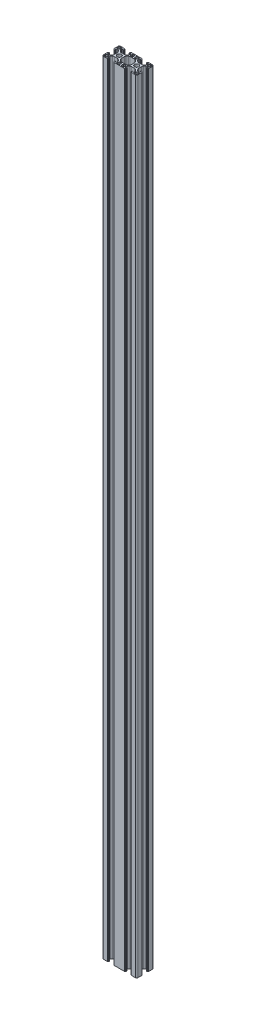
SolidWorks part; units mm, degrees
ref_plane "Спереди" through (0, 0, 0) normal (0, 0, 1) x (1, 0, 0)
ref_plane "Сверху" through (0, 0, 0) normal (0, 1, 0) x (1, 0, 0)
ref_plane "Справа" through (0, 0, 0) normal (1, 0, 0) x (0, 0, -1)
sketch "Эскиз2" plane through (0, 0, 0) normal (0, 1, 0) x (1, 0, 0)
  line L0 (-2.2449, 7.8949) -> (-0.7449, 6.3949) construction
  line L1 (19.2551, 9.3949) -> (16.2551, 6.3949) construction
  line L2 (-9.8449, 0.2949) -> (0.1551, 10.2949) construction
  line L3 (10.1551, 4.2949) -> (12.0538, 4.2949)
  line L4 (10.1551, 0.2949) -> (20.1551, 10.2949) construction
  line L5 (17.7551, 7.8949) -> (16.2551, 9.3949) construction
  line L6 (13.4681, 4.8807) -> (14.7693, 6.1819)
  line L7 (17.0551, 6.3949) -> (18.4551, 6.3949)
  line L8 (16.2551, 7.1949) -> (16.2551, 8.5949)
  line L9 (18.4551, 9.3949) -> (17.0551, 9.3949)
  line L10 (15.3551, 8.4949) -> (15.3551, 7.5961)
  line L11 (13.9183, 8.3681) -> (14.3986, 8.8485)
  line L12 (13.3551, 9.844) -> (13.8551, 9.844)
  line L13 (13.7415, 8.2949) -> (13.4551, 8.2949)
  line L14 (14.7522, 8.9949) -> (14.8551, 8.9949)
  line L15 (13.8551, 10.1449) -> (13.8551, 9.844)
  line L16 (13.2051, 9.694) -> (13.2051, 8.5449)
  line L17 (18.6551, 10.2949) -> (14.0051, 10.2949)
  line L18 (19.2551, 8.5949) -> (19.2551, 7.1949)
  line L19 (20.1551, 8.7949) -> (20.1551, 4.1449)
  line L20 (19.5541, 3.3449) -> (18.4051, 3.3449)
  line L21 (20.0051, 3.9949) -> (19.7041, 3.9949)
  line L22 (18.8551, 4.892) -> (18.8551, 4.9949)
  line L23 (18.1551, 3.8814) -> (18.1551, 3.5949)
  line L24 (19.7041, 3.4949) -> (19.7041, 3.9949)
  line L25 (18.2283, 4.0581) -> (18.7086, 4.5385)
  line L26 (18.3551, 5.4949) -> (17.4563, 5.4949)
  line L27 (14.7409, 3.6079) -> (16.0421, 4.9091)
  line L28 (14.1551, 0.2949) -> (14.1551, 2.1937)
  line L29 (14.1551, 0.2949) -> (14.1551, -1.6039)
  line L30 (14.7409, -3.0181) -> (16.0421, -4.3193)
  line L31 (16.2551, -6.6051) -> (16.2551, -8.0051)
  line L32 (17.0551, -5.8051) -> (18.4551, -5.8051)
  line L33 (19.2551, -8.0051) -> (19.2551, -6.6051)
  line L34 (18.3551, -4.9051) -> (17.4563, -4.9051)
  line L35 (18.2283, -3.4683) -> (18.7086, -3.9486)
  line L36 (19.7041, -2.9051) -> (19.7041, -3.4051)
  line L37 (18.1551, -3.2915) -> (18.1551, -3.0051)
  line L38 (18.8551, -4.3022) -> (18.8551, -4.4051)
  line L39 (20.0051, -3.4051) -> (19.7041, -3.4051)
  line L40 (19.5541, -2.7551) -> (18.4051, -2.7551)
  line L41 (20.1551, -8.2051) -> (20.1551, -3.5551)
  line L42 (18.4551, -8.8051) -> (17.0551, -8.8051)
  line L43 (18.6551, -9.7051) -> (14.0051, -9.7051)
  line L44 (13.2051, -9.1042) -> (13.2051, -7.9551)
  line L45 (13.8551, -9.5551) -> (13.8551, -9.2542)
  line L46 (14.7522, -8.4051) -> (14.8551, -8.4051)
  line L47 (13.7415, -7.7051) -> (13.4551, -7.7051)
  line L48 (13.3551, -9.2542) -> (13.8551, -9.2542)
  line L49 (13.9183, -7.7783) -> (14.3986, -8.2586)
  line L50 (15.3551, -7.9051) -> (15.3551, -7.0063)
  line L51 (13.4681, -4.2909) -> (14.7693, -5.5921)
  line L52 (10.1551, -3.7051) -> (12.0538, -3.7051)
  line L53 (19.2551, -8.8051) -> (16.2551, -5.8051) construction
  line L54 (10.1551, 0.2949) -> (20.1551, -9.7051) construction
  line L55 (17.7551, -7.3051) -> (19.2551, -5.8051) construction
  line L56 (10.1551, -3.7051) -> (8.2563, -3.7051)
  line L57 (6.8421, -4.2909) -> (5.5409, -5.5921)
  line L58 (3.2551, -5.8051) -> (1.8551, -5.8051)
  line L59 (4.0551, -6.6051) -> (4.0551, -8.0051)
  line L60 (1.8551, -8.8051) -> (3.2551, -8.8051)
  line L61 (4.9551, -7.9051) -> (4.9551, -7.0063)
  line L62 (6.3918, -7.7783) -> (5.9115, -8.2586)
  line L63 (6.9551, -9.2542) -> (6.4551, -9.2542)
  line L64 (6.5686, -7.7051) -> (6.8551, -7.7051)
  line L65 (5.558, -8.4051) -> (5.4551, -8.4051)
  line L66 (6.4551, -9.5551) -> (6.4551, -9.2542)
  line L67 (7.1051, -9.1042) -> (7.1051, -7.9551)
  line L68 (1.6551, -9.7051) -> (6.3051, -9.7051)
  line L69 (1.0551, -8.0051) -> (1.0551, -6.6051)
  line L70 (1.9551, -4.9051) -> (2.8538, -4.9051)
  line L71 (5.5693, -3.0181) -> (4.2681, -4.3193)
  line L72 (6.1551, 0.2949) -> (6.1551, -1.6039)
  line L73 (-0.7449, 9.3949) -> (-3.7449, 6.3949) construction
  line L74 (1.0551, -8.8051) -> (4.0551, -5.8051) construction
  line L75 (-2.2449, -7.3051) -> (-3.7449, -8.8051) construction
  line L76 (10.1551, 0.2949) -> (0.1551, -9.7051) construction
  line L77 (2.5551, -7.3051) -> (4.0551, -8.8051) construction
  line L78 (6.1551, 0.2949) -> (6.1551, 2.1937)
  line L79 (5.5693, 3.6079) -> (4.2681, 4.9091)
  line L80 (4.0551, 7.1949) -> (4.0551, 8.5949)
  line L81 (3.2551, 6.3949) -> (1.8551, 6.3949)
  line L82 (1.0551, 8.5949) -> (1.0551, 7.1949)
  line L83 (1.9551, 5.4949) -> (2.8538, 5.4949)
  line L84 (1.8551, 9.3949) -> (3.2551, 9.3949)
  line L85 (1.6551, 10.2949) -> (6.3051, 10.2949)
  line L86 (7.1051, 9.694) -> (7.1051, 8.5449)
  line L87 (6.4551, 10.1449) -> (6.4551, 9.844)
  line L88 (5.558, 8.9949) -> (5.4551, 8.9949)
  line L89 (6.5686, 8.2949) -> (6.8551, 8.2949)
  line L90 (6.9551, 9.844) -> (6.4551, 9.844)
  line L91 (6.3918, 8.3681) -> (5.9115, 8.8485)
  line L92 (4.9551, 8.4949) -> (4.9551, 7.5961)
  line L93 (6.8421, 4.8807) -> (5.5409, 6.1819)
  line L94 (10.1551, 4.2949) -> (8.2563, 4.2949)
  line L95 (-1.609, 0.2949) -> (21.6594, 0.2949) construction
  line L96 (1.0551, 9.3949) -> (4.0551, 6.3949) construction
  line L97 (10.1551, -11.7915) -> (10.1551, 11.0139) construction
  line L98 (10.1551, 0.2949) -> (0.1551, 10.2949) construction
  line L99 (2.5551, 7.8949) -> (1.0551, 6.3949) construction
  line L100 (-9.8449, 0.2949) -> (0.1551, -9.7051) construction
  line L101 (-0.7449, -8.8051) -> (-3.7449, -5.8051) construction
  line L102 (-17.4449, -7.3051) -> (-18.9449, -5.8051) construction
  line L103 (-9.8449, 0.2949) -> (-19.8449, -9.7051) construction
  line L104 (-18.9449, -8.8051) -> (-15.9449, -5.8051) construction
  line L105 (-17.4449, 7.8949) -> (-15.9449, 9.3949) construction
  line L106 (-9.8449, 0.2949) -> (-19.8449, 10.2949) construction
  line L107 (-18.9449, 9.3949) -> (-15.9449, 6.3949) construction
  line L108 (-9.8449, 4.2949) -> (-7.9462, 4.2949)
  line L109 (-6.5319, 4.8807) -> (-5.2307, 6.1819)
  line L110 (-4.6449, 8.4949) -> (-4.6449, 7.5961)
  line L111 (-6.0817, 8.3681) -> (-5.6014, 8.8485)
  line L112 (-6.6449, 9.844) -> (-6.1449, 9.844)
  line L113 (-6.2585, 8.2949) -> (-6.5449, 8.2949)
  line L114 (-5.2478, 8.9949) -> (-5.1449, 8.9949)
  line L115 (-6.1449, 10.1449) -> (-6.1449, 9.844)
  line L116 (-6.7949, 9.694) -> (-6.7949, 8.5449)
  line L117 (-1.3449, 10.2949) -> (-5.9949, 10.2949)
  line L118 (-1.5449, 9.3949) -> (-2.9449, 9.3949)
  line L119 (-1.6449, 5.4949) -> (-2.5437, 5.4949)
  line L120 (-0.7449, 8.5949) -> (-0.7449, 7.1949)
  line L121 (-2.9449, 6.3949) -> (-1.5449, 6.3949)
  line L122 (-3.7449, 7.1949) -> (-3.7449, 8.5949)
  line L123 (-5.2591, 3.6079) -> (-3.9579, 4.9091)
  line L124 (-5.8449, 0.2949) -> (-5.8449, 2.1937)
  line L125 (-5.8449, 0.2949) -> (-5.8449, -1.6039)
  line L126 (-5.2591, -3.0181) -> (-3.9579, -4.3193)
  line L127 (-1.6449, -4.9051) -> (-2.5437, -4.9051)
  line L128 (-0.7449, -8.0051) -> (-0.7449, -6.6051)
  line L129 (-1.3449, -9.7051) -> (-5.9949, -9.7051)
  line L130 (-6.7949, -9.1042) -> (-6.7949, -7.9551)
  line L131 (-6.1449, -9.5551) -> (-6.1449, -9.2542)
  line L132 (-5.2478, -8.4051) -> (-5.1449, -8.4051)
  line L133 (-6.2585, -7.7051) -> (-6.5449, -7.7051)
  line L134 (-6.6449, -9.2542) -> (-6.1449, -9.2542)
  line L135 (-6.0817, -7.7783) -> (-5.6014, -8.2586)
  line L136 (-4.6449, -7.9051) -> (-4.6449, -7.0063)
  line L137 (-1.5449, -8.8051) -> (-2.9449, -8.8051)
  line L138 (-3.7449, -6.6051) -> (-3.7449, -8.0051)
  line L139 (-2.9449, -5.8051) -> (-1.5449, -5.8051)
  line L140 (-6.5319, -4.2909) -> (-5.2307, -5.5921)
  line L141 (-9.8449, -3.7051) -> (-7.9462, -3.7051)
  line L142 (-9.8449, -3.7051) -> (-11.7437, -3.7051)
  line L143 (-13.1579, -4.2909) -> (-14.4591, -5.5921)
  line L144 (-15.0449, -7.9051) -> (-15.0449, -7.0063)
  line L145 (-13.6082, -7.7783) -> (-14.0885, -8.2586)
  line L146 (-13.0449, -9.2542) -> (-13.5449, -9.2542)
  line L147 (-13.4314, -7.7051) -> (-13.1449, -7.7051)
  line L148 (-14.442, -8.4051) -> (-14.5449, -8.4051)
  line L149 (-13.5449, -9.5551) -> (-13.5449, -9.2542)
  line L150 (-12.8949, -9.1042) -> (-12.8949, -7.9551)
  line L151 (-18.3449, -9.7051) -> (-13.6949, -9.7051)
  line L152 (-18.1449, -8.8051) -> (-16.7449, -8.8051)
  line L153 (-19.8449, -8.2051) -> (-19.8449, -3.5551)
  line L154 (-19.244, -2.7551) -> (-18.0949, -2.7551)
  line L155 (-19.6949, -3.4051) -> (-19.394, -3.4051)
  line L156 (-18.5449, -4.3022) -> (-18.5449, -4.4051)
  line L157 (-17.8449, -3.2915) -> (-17.8449, -3.0051)
  line L158 (-19.394, -2.9051) -> (-19.394, -3.4051)
  line L159 (-17.9182, -3.4683) -> (-18.3985, -3.9486)
  line L160 (-18.0449, -4.9051) -> (-17.1462, -4.9051)
  line L161 (-18.9449, -8.0051) -> (-18.9449, -6.6051)
  line L162 (-16.7449, -5.8051) -> (-18.1449, -5.8051)
  line L163 (-15.9449, -6.6051) -> (-15.9449, -8.0051)
  line L164 (-14.4307, -3.0181) -> (-15.7319, -4.3193)
  line L165 (-13.8449, 0.2949) -> (-13.8449, -1.6039)
  line L166 (-13.8449, 0.2949) -> (-13.8449, 2.1937)
  line L167 (-14.4307, 3.6079) -> (-15.7319, 4.9091)
  line L168 (-18.0449, 5.4949) -> (-17.1462, 5.4949)
  line L169 (-17.9182, 4.0581) -> (-18.3985, 4.5385)
  line L170 (-19.394, 3.4949) -> (-19.394, 3.9949)
  line L171 (-17.8449, 3.8814) -> (-17.8449, 3.5949)
  line L172 (-18.5449, 4.892) -> (-18.5449, 4.9949)
  line L173 (-19.6949, 3.9949) -> (-19.394, 3.9949)
  line L174 (-19.244, 3.3449) -> (-18.0949, 3.3449)
  line L175 (-19.8449, 8.7949) -> (-19.8449, 4.1449)
  line L176 (-18.9449, 8.5949) -> (-18.9449, 7.1949)
  line L177 (-18.3449, 10.2949) -> (-13.6949, 10.2949)
  line L178 (-12.8949, 9.694) -> (-12.8949, 8.5449)
  line L179 (-13.5449, 10.1449) -> (-13.5449, 9.844)
  line L180 (-14.442, 8.9949) -> (-14.5449, 8.9949)
  line L181 (-13.4314, 8.2949) -> (-13.1449, 8.2949)
  line L182 (-13.0449, 9.844) -> (-13.5449, 9.844)
  line L183 (-13.6082, 8.3681) -> (-14.0885, 8.8485)
  line L184 (-15.0449, 8.4949) -> (-15.0449, 7.5961)
  line L185 (-18.1449, 9.3949) -> (-16.7449, 9.3949)
  line L186 (-15.9449, 7.1949) -> (-15.9449, 8.5949)
  line L187 (-16.7449, 6.3949) -> (-18.1449, 6.3949)
  line L188 (-13.1579, 4.8807) -> (-14.4591, 6.1819)
  line L189 (-9.8449, 4.2949) -> (-11.7437, 4.2949)
  line L190 (-1.3449, -9.7051) -> (1.6551, -9.7051)
  line L191 (-1.6449, -4.9051) -> (1.9551, -4.9051)
  line L192 (-1.6449, 5.4949) -> (1.9551, 5.4949)
  line L193 (-1.3449, 10.2949) -> (1.6551, 10.2949)
  arc A0 (19.2551, 8.5949) -> (18.4551, 9.3949) centre (18.4551, 8.5949) ccw
  arc A1 (17.0551, 9.3949) -> (16.2551, 8.5949) centre (17.0551, 8.5949) ccw
  arc A2 (17.0551, 6.3949) -> (16.2551, 7.1949) centre (17.0551, 7.1949) cw
  arc A3 (18.6551, 10.2949) -> (20.1551, 8.7949) centre (18.6551, 8.7949) cw
  arc A4 (13.3551, 9.844) -> (13.2051, 9.694) centre (13.3551, 9.694) ccw
  arc A5 (14.0051, 10.2949) -> (13.8551, 10.1449) centre (14.0051, 10.1449) ccw
  arc A6 (13.7415, 8.2949) -> (13.9183, 8.3681) centre (13.7415, 8.5449) ccw
  arc A7 (13.4551, 8.2949) -> (13.2051, 8.5449) centre (13.4551, 8.5449) cw
  arc A8 (14.3986, 8.8485) -> (14.7522, 8.9949) centre (14.7522, 8.4949) cw
  arc A9 (14.8551, 8.9949) -> (15.3551, 8.4949) centre (14.8551, 8.4949) cw
  arc A10 (12.6551, 0.2949) -> (10.1551, 2.7949) centre (10.1551, 0.2949) ccw
  arc A11 (12.0538, 4.2949) -> (13.4681, 4.8807) centre (12.0538, 6.2949) ccw
  arc A12 (15.3551, 7.5961) -> (14.7693, 6.1819) centre (13.3551, 7.5961) cw
  arc A13 (19.2551, 7.1949) -> (18.4551, 6.3949) centre (18.4551, 7.1949) cw
  arc A14 (18.8551, 4.9949) -> (18.3551, 5.4949) centre (18.3551, 4.9949) ccw
  arc A15 (18.7086, 4.5385) -> (18.8551, 4.892) centre (18.3551, 4.892) ccw
  arc A16 (18.1551, 3.5949) -> (18.4051, 3.3449) centre (18.4051, 3.5949) ccw
  arc A17 (18.1551, 3.8814) -> (18.2283, 4.0581) centre (18.4051, 3.8814) cw
  arc A18 (20.1551, 4.1449) -> (20.0051, 3.9949) centre (20.0051, 4.1449) cw
  arc A19 (19.7041, 3.4949) -> (19.5541, 3.3449) centre (19.5541, 3.4949) cw
  arc A20 (17.4563, 5.4949) -> (16.0421, 4.9091) centre (17.4563, 3.4949) ccw
  arc A21 (14.1551, 2.1937) -> (14.7409, 3.6079) centre (16.1551, 2.1937) cw
  arc A22 (18.4551, -8.8051) -> (19.2551, -8.0051) centre (18.4551, -8.0051) ccw
  arc A23 (19.2551, -6.6051) -> (18.4551, -5.8051) centre (18.4551, -6.6051) ccw
  arc A24 (16.2551, -6.6051) -> (17.0551, -5.8051) centre (17.0551, -6.6051) cw
  arc A25 (20.1551, -8.2051) -> (18.6551, -9.7051) centre (18.6551, -8.2051) cw
  arc A26 (19.7041, -2.9051) -> (19.5541, -2.7551) centre (19.5541, -2.9051) ccw
  arc A27 (20.1551, -3.5551) -> (20.0051, -3.4051) centre (20.0051, -3.5551) ccw
  arc A28 (18.1551, -3.2915) -> (18.2283, -3.4683) centre (18.4051, -3.2915) ccw
  arc A29 (18.1551, -3.0051) -> (18.4051, -2.7551) centre (18.4051, -3.0051) cw
  arc A30 (18.7086, -3.9486) -> (18.8551, -4.3022) centre (18.3551, -4.3022) cw
  arc A31 (18.8551, -4.4051) -> (18.3551, -4.9051) centre (18.3551, -4.4051) cw
  arc A32 (10.1551, -2.2051) -> (12.6551, 0.2949) centre (10.1551, 0.2949) ccw
  arc A33 (14.1551, -1.6039) -> (14.7409, -3.0181) centre (16.1551, -1.6039) ccw
  arc A34 (17.4563, -4.9051) -> (16.0421, -4.3193) centre (17.4563, -2.9051) cw
  arc A35 (17.0551, -8.8051) -> (16.2551, -8.0051) centre (17.0551, -8.0051) cw
  arc A36 (14.8551, -8.4051) -> (15.3551, -7.9051) centre (14.8551, -7.9051) ccw
  arc A37 (14.3986, -8.2586) -> (14.7522, -8.4051) centre (14.7522, -7.9051) ccw
  arc A38 (13.4551, -7.7051) -> (13.2051, -7.9551) centre (13.4551, -7.9551) ccw
  arc A39 (13.7415, -7.7051) -> (13.9183, -7.7783) centre (13.7415, -7.9551) cw
  arc A40 (14.0051, -9.7051) -> (13.8551, -9.5551) centre (14.0051, -9.5551) cw
  arc A41 (13.3551, -9.2542) -> (13.2051, -9.1042) centre (13.3551, -9.1042) cw
  arc A42 (15.3551, -7.0063) -> (14.7693, -5.5921) centre (13.3551, -7.0063) ccw
  arc A43 (12.0538, -3.7051) -> (13.4681, -4.2909) centre (12.0538, -5.7051) cw
  arc A44 (1.0551, -8.0051) -> (1.8551, -8.8051) centre (1.8551, -8.0051) ccw
  arc A45 (3.2551, -8.8051) -> (4.0551, -8.0051) centre (3.2551, -8.0051) ccw
  arc A46 (3.2551, -5.8051) -> (4.0551, -6.6051) centre (3.2551, -6.6051) cw
  arc A47 (6.9551, -9.2542) -> (7.1051, -9.1042) centre (6.9551, -9.1042) ccw
  arc A48 (6.3051, -9.7051) -> (6.4551, -9.5551) centre (6.3051, -9.5551) ccw
  arc A49 (6.5686, -7.7051) -> (6.3918, -7.7783) centre (6.5686, -7.9551) ccw
  arc A50 (6.8551, -7.7051) -> (7.1051, -7.9551) centre (6.8551, -7.9551) cw
  arc A51 (5.9115, -8.2586) -> (5.558, -8.4051) centre (5.558, -7.9051) cw
  arc A52 (5.4551, -8.4051) -> (4.9551, -7.9051) centre (5.4551, -7.9051) cw
  arc A53 (7.6551, 0.2949) -> (10.1551, -2.2051) centre (10.1551, 0.2949) ccw
  arc A54 (8.2563, -3.7051) -> (6.8421, -4.2909) centre (8.2563, -5.7051) ccw
  arc A55 (4.9551, -7.0063) -> (5.5409, -5.5921) centre (6.9551, -7.0063) cw
  arc A56 (1.0551, -6.6051) -> (1.8551, -5.8051) centre (1.8551, -6.6051) cw
  arc A57 (2.8538, -4.9051) -> (4.2681, -4.3193) centre (2.8538, -2.9051) ccw
  arc A58 (6.1551, -1.6039) -> (5.5693, -3.0181) centre (4.1551, -1.6039) cw
  arc A59 (1.8551, 9.3949) -> (1.0551, 8.5949) centre (1.8551, 8.5949) ccw
  arc A60 (1.0551, 7.1949) -> (1.8551, 6.3949) centre (1.8551, 7.1949) ccw
  arc A61 (4.0551, 7.1949) -> (3.2551, 6.3949) centre (3.2551, 7.1949) cw
  arc A62 (10.1551, 2.7949) -> (7.6551, 0.2949) centre (10.1551, 0.2949) ccw
  arc A63 (6.1551, 2.1937) -> (5.5693, 3.6079) centre (4.1551, 2.1937) ccw
  arc A64 (2.8538, 5.4949) -> (4.2681, 4.9091) centre (2.8538, 3.4949) cw
  arc A65 (3.2551, 9.3949) -> (4.0551, 8.5949) centre (3.2551, 8.5949) cw
  arc A66 (5.4551, 8.9949) -> (4.9551, 8.4949) centre (5.4551, 8.4949) ccw
  arc A67 (5.9115, 8.8485) -> (5.558, 8.9949) centre (5.558, 8.4949) ccw
  arc A68 (6.8551, 8.2949) -> (7.1051, 8.5449) centre (6.8551, 8.5449) ccw
  arc A69 (6.5686, 8.2949) -> (6.3918, 8.3681) centre (6.5686, 8.5449) cw
  arc A70 (6.3051, 10.2949) -> (6.4551, 10.1449) centre (6.3051, 10.1449) cw
  arc A71 (6.9551, 9.844) -> (7.1051, 9.694) centre (6.9551, 9.694) cw
  arc A72 (4.9551, 7.5961) -> (5.5409, 6.1819) centre (6.9551, 7.5961) ccw
  arc A73 (8.2563, 4.2949) -> (6.8421, 4.8807) centre (8.2563, 6.2949) cw
  arc A74 (-7.9462, 4.2949) -> (-6.5319, 4.8807) centre (-7.9462, 6.2949) ccw
  arc A75 (-4.6449, 7.5961) -> (-5.2307, 6.1819) centre (-6.6449, 7.5961) cw
  arc A76 (-6.6449, 9.844) -> (-6.7949, 9.694) centre (-6.6449, 9.694) ccw
  arc A77 (-5.9949, 10.2949) -> (-6.1449, 10.1449) centre (-5.9949, 10.1449) ccw
  arc A78 (-6.2585, 8.2949) -> (-6.0817, 8.3681) centre (-6.2585, 8.5449) ccw
  arc A79 (-6.5449, 8.2949) -> (-6.7949, 8.5449) centre (-6.5449, 8.5449) cw
  arc A80 (-5.6014, 8.8485) -> (-5.2478, 8.9949) centre (-5.2478, 8.4949) cw
  arc A81 (-5.1449, 8.9949) -> (-4.6449, 8.4949) centre (-5.1449, 8.4949) cw
  arc A82 (-2.9449, 9.3949) -> (-3.7449, 8.5949) centre (-2.9449, 8.5949) ccw
  arc A83 (-2.5437, 5.4949) -> (-3.9579, 4.9091) centre (-2.5437, 3.4949) ccw
  arc A84 (-5.8449, 2.1937) -> (-5.2591, 3.6079) centre (-3.8449, 2.1937) cw
  arc A85 (-9.8449, 2.7949) -> (-7.3449, 0.2949) centre (-9.8449, 0.2949) cw
  arc A86 (-3.7449, 7.1949) -> (-2.9449, 6.3949) centre (-2.9449, 7.1949) ccw
  arc A87 (-0.7449, 7.1949) -> (-1.5449, 6.3949) centre (-1.5449, 7.1949) cw
  arc A88 (-1.5449, 9.3949) -> (-0.7449, 8.5949) centre (-1.5449, 8.5949) cw
  arc A89 (-5.8449, -1.6039) -> (-5.2591, -3.0181) centre (-3.8449, -1.6039) ccw
  arc A90 (-2.5437, -4.9051) -> (-3.9579, -4.3193) centre (-2.5437, -2.9051) cw
  arc A91 (-0.7449, -6.6051) -> (-1.5449, -5.8051) centre (-1.5449, -6.6051) ccw
  arc A92 (-4.6449, -7.0063) -> (-5.2307, -5.5921) centre (-6.6449, -7.0063) ccw
  arc A93 (-7.9462, -3.7051) -> (-6.5319, -4.2909) centre (-7.9462, -5.7051) cw
  arc A94 (-7.3449, 0.2949) -> (-9.8449, -2.2051) centre (-9.8449, 0.2949) cw
  arc A95 (-5.1449, -8.4051) -> (-4.6449, -7.9051) centre (-5.1449, -7.9051) ccw
  arc A96 (-5.6014, -8.2586) -> (-5.2478, -8.4051) centre (-5.2478, -7.9051) ccw
  arc A97 (-6.5449, -7.7051) -> (-6.7949, -7.9551) centre (-6.5449, -7.9551) ccw
  arc A98 (-6.2585, -7.7051) -> (-6.0817, -7.7783) centre (-6.2585, -7.9551) cw
  arc A99 (-5.9949, -9.7051) -> (-6.1449, -9.5551) centre (-5.9949, -9.5551) cw
  arc A100 (-6.6449, -9.2542) -> (-6.7949, -9.1042) centre (-6.6449, -9.1042) cw
  arc A101 (-2.9449, -5.8051) -> (-3.7449, -6.6051) centre (-2.9449, -6.6051) ccw
  arc A102 (-2.9449, -8.8051) -> (-3.7449, -8.0051) centre (-2.9449, -8.0051) cw
  arc A103 (-0.7449, -8.0051) -> (-1.5449, -8.8051) centre (-1.5449, -8.0051) cw
  arc A104 (-11.7437, -3.7051) -> (-13.1579, -4.2909) centre (-11.7437, -5.7051) ccw
  arc A105 (-15.0449, -7.0063) -> (-14.4591, -5.5921) centre (-13.0449, -7.0063) cw
  arc A106 (-13.0449, -9.2542) -> (-12.8949, -9.1042) centre (-13.0449, -9.1042) ccw
  arc A107 (-13.6949, -9.7051) -> (-13.5449, -9.5551) centre (-13.6949, -9.5551) ccw
  arc A108 (-13.4314, -7.7051) -> (-13.6082, -7.7783) centre (-13.4314, -7.9551) ccw
  arc A109 (-13.1449, -7.7051) -> (-12.8949, -7.9551) centre (-13.1449, -7.9551) cw
  arc A110 (-14.0885, -8.2586) -> (-14.442, -8.4051) centre (-14.442, -7.9051) cw
  arc A111 (-14.5449, -8.4051) -> (-15.0449, -7.9051) centre (-14.5449, -7.9051) cw
  arc A112 (-16.7449, -8.8051) -> (-15.9449, -8.0051) centre (-16.7449, -8.0051) ccw
  arc A113 (-17.1462, -4.9051) -> (-15.7319, -4.3193) centre (-17.1462, -2.9051) ccw
  arc A114 (-13.8449, -1.6039) -> (-14.4307, -3.0181) centre (-15.8449, -1.6039) cw
  arc A115 (-9.8449, -2.2051) -> (-12.3449, 0.2949) centre (-9.8449, 0.2949) cw
  arc A116 (-18.5449, -4.4051) -> (-18.0449, -4.9051) centre (-18.0449, -4.4051) ccw
  arc A117 (-18.3985, -3.9486) -> (-18.5449, -4.3022) centre (-18.0449, -4.3022) ccw
  arc A118 (-17.8449, -3.0051) -> (-18.0949, -2.7551) centre (-18.0949, -3.0051) ccw
  arc A119 (-17.8449, -3.2915) -> (-17.9182, -3.4683) centre (-18.0949, -3.2915) cw
  arc A120 (-19.8449, -3.5551) -> (-19.6949, -3.4051) centre (-19.6949, -3.5551) cw
  arc A121 (-19.394, -2.9051) -> (-19.244, -2.7551) centre (-19.244, -2.9051) cw
  arc A122 (-19.8449, -8.2051) -> (-18.3449, -9.7051) centre (-18.3449, -8.2051) ccw
  arc A123 (-15.9449, -6.6051) -> (-16.7449, -5.8051) centre (-16.7449, -6.6051) ccw
  arc A124 (-18.9449, -6.6051) -> (-18.1449, -5.8051) centre (-18.1449, -6.6051) cw
  arc A125 (-18.1449, -8.8051) -> (-18.9449, -8.0051) centre (-18.1449, -8.0051) cw
  arc A126 (-13.8449, 2.1937) -> (-14.4307, 3.6079) centre (-15.8449, 2.1937) ccw
  arc A127 (-17.1462, 5.4949) -> (-15.7319, 4.9091) centre (-17.1462, 3.4949) cw
  arc A128 (-19.394, 3.4949) -> (-19.244, 3.3449) centre (-19.244, 3.4949) ccw
  arc A129 (-19.8449, 4.1449) -> (-19.6949, 3.9949) centre (-19.6949, 4.1449) ccw
  arc A130 (-17.8449, 3.8814) -> (-17.9182, 4.0581) centre (-18.0949, 3.8814) ccw
  arc A131 (-17.8449, 3.5949) -> (-18.0949, 3.3449) centre (-18.0949, 3.5949) cw
  arc A132 (-18.3985, 4.5385) -> (-18.5449, 4.892) centre (-18.0449, 4.892) cw
  arc A133 (-18.5449, 4.9949) -> (-18.0449, 5.4949) centre (-18.0449, 4.9949) cw
  arc A134 (-18.9449, 7.1949) -> (-18.1449, 6.3949) centre (-18.1449, 7.1949) ccw
  arc A135 (-15.0449, 7.5961) -> (-14.4591, 6.1819) centre (-13.0449, 7.5961) ccw
  arc A136 (-11.7437, 4.2949) -> (-13.1579, 4.8807) centre (-11.7437, 6.2949) cw
  arc A137 (-12.3449, 0.2949) -> (-9.8449, 2.7949) centre (-9.8449, 0.2949) cw
  arc A138 (-14.5449, 8.9949) -> (-15.0449, 8.4949) centre (-14.5449, 8.4949) ccw
  arc A139 (-14.0885, 8.8485) -> (-14.442, 8.9949) centre (-14.442, 8.4949) ccw
  arc A140 (-13.1449, 8.2949) -> (-12.8949, 8.5449) centre (-13.1449, 8.5449) ccw
  arc A141 (-13.4314, 8.2949) -> (-13.6082, 8.3681) centre (-13.4314, 8.5449) cw
  arc A142 (-13.6949, 10.2949) -> (-13.5449, 10.1449) centre (-13.6949, 10.1449) cw
  arc A143 (-13.0449, 9.844) -> (-12.8949, 9.694) centre (-13.0449, 9.694) cw
  arc A144 (-18.3449, 10.2949) -> (-19.8449, 8.7949) centre (-18.3449, 8.7949) ccw
  arc A145 (-16.7449, 6.3949) -> (-15.9449, 7.1949) centre (-16.7449, 7.1949) ccw
  arc A146 (-16.7449, 9.3949) -> (-15.9449, 8.5949) centre (-16.7449, 8.5949) cw
  arc A147 (-18.9449, 8.5949) -> (-18.1449, 9.3949) centre (-18.1449, 8.5949) cw
  point P0 (10.1551, 0.2949)
  point P12 (10.1551, 0.2949)
  point P45 (18.8551, 3.9949)
  point P104 (13.8551, -8.4051)
  point P155 (13.8551, 8.9949)
  point P163 (18.8551, -3.4051)
  point P164 (10.1551, -3.6294)
  point P166 (10.1551, 0.2949)
  point P224 (6.4551, -8.4051)
  point P225 (6.2308, 0.2949)
  point P227 (10.1551, 0.2949)
  point P267 (6.4551, 8.9949)
  point P272 (14.0793, 0.2949)
  point P288 (10.1551, 4.2192)
  point P290 (10.1551, 0.2949)
  point P515 (-9.8449, 4.2192)
  point P516 (-13.7692, 0.2949)
  point P517 (-6.1449, 8.9949)
  point P518 (-5.9207, 0.2949)
  point P519 (-6.1449, -8.4051)
  point P520 (-9.8449, -3.6294)
  point P521 (-18.5449, -3.4051)
  point P522 (-13.5449, 8.9949)
  point P523 (-13.5449, -8.4051)
  point P524 (-18.5449, 3.9949)
  dimension "D3" = 5
  dimension "D6" = 2
  dimension "D1" = 2
  dimension "D2" = 6
  dimension "D4" = 4
  dimension "D5" = 0.9
extrude "Бобышка-Вытянуть1" add sketch "Эскиз2" along normal blind 905
